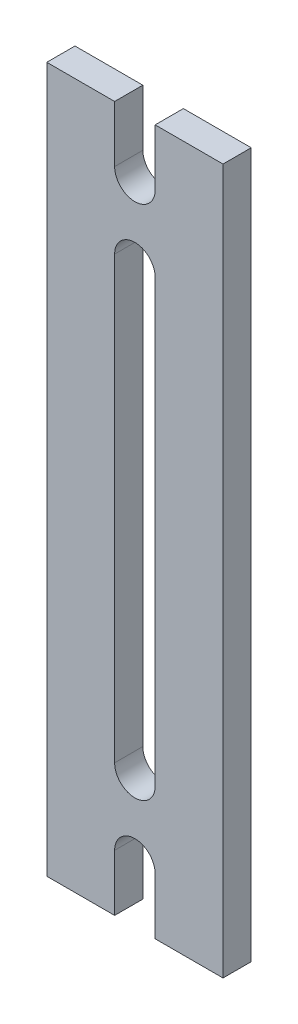
SolidWorks part; units mm, degrees
ref_plane "Front" through (0, 0, 0) normal (0, 0, 1) x (1, 0, 0)
ref_plane "Top" through (0, 0, 0) normal (0, 1, 0) x (1, 0, 0)
ref_plane "Right" through (0, 0, 0) normal (1, 0, 0) x (0, 0, -1)
sketch "Sketch1" plane through (0, 0, 0) normal (0, 0, 1) x (1, 0, 0)
  line L1 (-5, -20) -> (5, -20)
  line L2 (-5, -20) -> (-5, 20)
  line L3 (-5, 20) -> (5, 20)
  line L4 (5, -20) -> (5, 20)
  line L5 (-5, -20) -> (5, 20) construction
  line L6 (-5, 20) -> (5, -20) construction
  point P0 (0, 0)
  dimension "D1" = 10
  dimension "D2" = 40
extrude "Boss-Extrude1" add sketch "Sketch1" along normal blind 1.6
sketch "Sketch3" plane through (0, 0, 1.6) normal (0, 0, 1) x (1, 0, 0)
  line L0 (0, 0) -> (0, 7.5101) construction
  line L1 (0, 12.5) -> (0, -12.5) construction
  line L2 (1.15, 12.5) -> (1.15, -12.5)
  line L3 (-1.15, 12.5) -> (-1.15, -12.5)
  line L4 (0, 41.8) -> (0, 16.8) construction
  line L5 (1.15, 41.8) -> (1.15, 16.8)
  line L6 (-1.15, 41.8) -> (-1.15, 16.8)
  line L7 (0, -16.8) -> (0, -41.8) construction
  line L8 (1.15, -16.8) -> (1.15, -41.8)
  line L9 (-1.15, -16.8) -> (-1.15, -41.8)
  arc A0 (1.15, 12.5) -> (-1.15, 12.5) centre (0, 12.5) ccw
  arc A1 (-1.15, -12.5) -> (1.15, -12.5) centre (0, -12.5) ccw
  arc A2 (1.15, 41.8) -> (-1.15, 41.8) centre (0, 41.8) ccw
  arc A3 (-1.15, 16.8) -> (1.15, 16.8) centre (0, 16.8) ccw
  arc A4 (1.15, -16.8) -> (-1.15, -16.8) centre (0, -16.8) ccw
  arc A5 (-1.15, -41.8) -> (1.15, -41.8) centre (0, -41.8) ccw
  point P6 (0, 0)
  point P11 (0, 15.65)
  point P12 (0, 13.65)
  point P13 (0, 29.3)
  point P22 (0, -29.3)
  point P27 (0, -13.65)
  point P28 (0, -15.65)
  dimension "D3" = 2
  dimension "D1" = 25
  dimension "D2" = 2.3
  dimension "D4" = 2
extrude "Cut-Extrude1" cut sketch "Sketch3" against normal through all
